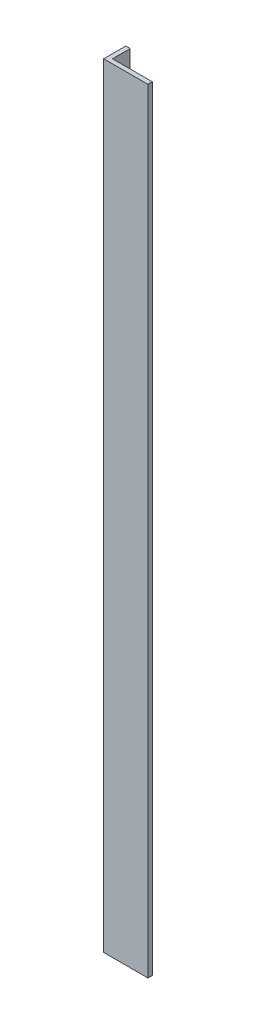
SolidWorks part; units mm, degrees
ref_plane "Front Plane" through (0, 0, 0) normal (0, 0, 1) x (1, 0, 0)
ref_plane "Top Plane" through (0, 0, 0) normal (0, 1, 0) x (1, 0, 0)
ref_plane "Right Plane" through (0, 0, 0) normal (1, 0, 0) x (0, 0, -1)
sketch "Sketch1" plane through (0, 0, 0) normal (0, 1, 0) x (1, 0, 0)
  line L0 (0, 0) -> (0, 10)
  line L1 (0, 10) -> (2, 10)
  line L2 (2, 10) -> (2, 2)
  line L3 (2, 2) -> (20, 2)
  line L4 (20, 2) -> (20, 0)
  line L5 (20, 0) -> (0, 0)
extrude "Boss-Extrude1" add sketch "Sketch1" along normal blind 350
